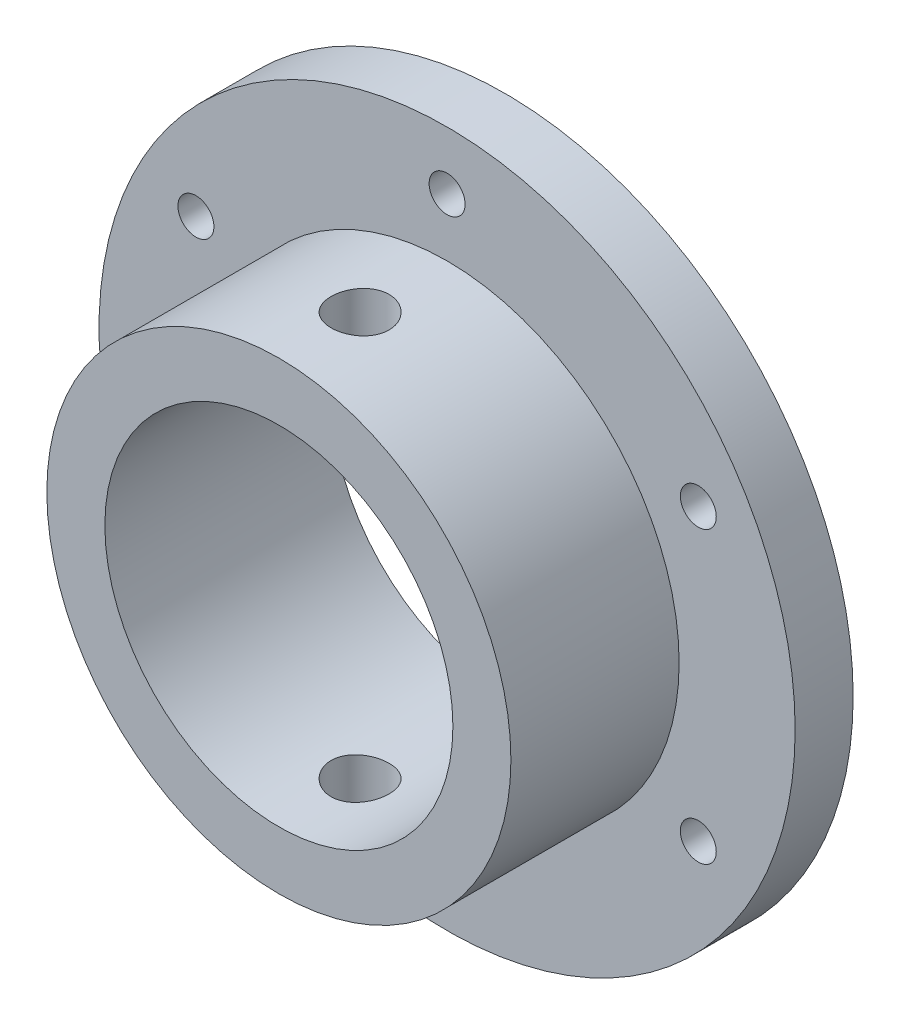
SolidWorks part; units mm, degrees
ref_plane "Front Plane" through (0, 0, 0) normal (0, 0, 1) x (1, 0, 0)
ref_plane "Top Plane" through (0, 0, 0) normal (0, 1, 0) x (1, 0, 0)
ref_plane "Right Plane" through (0, 0, 0) normal (1, 0, 0) x (0, 0, -1)
sketch "Sketch1" plane through (0, 0, 0) normal (0, 0, 1) x (1, 0, 0)
  circle A0 centre (0, 0) radius 30
  point P0 (0, 0)
  dimension "D1" = 60
extrude "Boss-Extrude1" add sketch "Sketch1" along normal blind 5
sketch "Sketch2" plane through (0, 0, 5) normal (0, 0, 1) x (1, 0, 0)
  circle A0 centre (0, 0) radius 20
  circle A1 centre (0, 0) radius 15
  dimension "D1" = 40
extrude "Boss-Extrude2" add sketch "Sketch2" along normal blind 14.5
sketch "Sketch3" plane through (0, 0, 5) normal (0, 0, 1) x (1, 0, 0)
  circle A0 centre (0, 0) radius 15
  dimension "D1" = 30
extrude "Cut-Extrude1" cut sketch "Sketch3" against normal blind 20
sketch "Sketch5" plane through (0, 0, 0) normal (0, 1, 0) x (1, 0, 0)
  line L0 (-20, -5) -> (20, -5) construction
  circle A0 centre (0, -12.5) radius 2.5
  dimension "D1" = 7.5
extrude "Cut-Extrude3" cut sketch "Sketch5" against normal through all both and the other way through all
sketch "Sketch6" plane through (0, 0, 5) normal (0, 0, 1) x (1, 0, 0)
  circle A0 centre (0, 0) radius 25 construction
  circle A1 centre (0, 25) radius 1.55
  circle A2 centre (21.6506, 12.5) radius 1.55
  circle A3 centre (21.6506, -12.5) radius 1.55
  circle A4 centre (0, -25) radius 1.55
  circle A5 centre (-21.6506, -12.5) radius 1.55
  circle A6 centre (-21.6506, 12.5) radius 1.55
  point P17 (0, 0)
  dimension "D1" = 50
  dimension "D2" = 6
  dimension "D3" = 3.1
extrude "Cut-Extrude4" cut sketch "Sketch6" against normal blind 10
